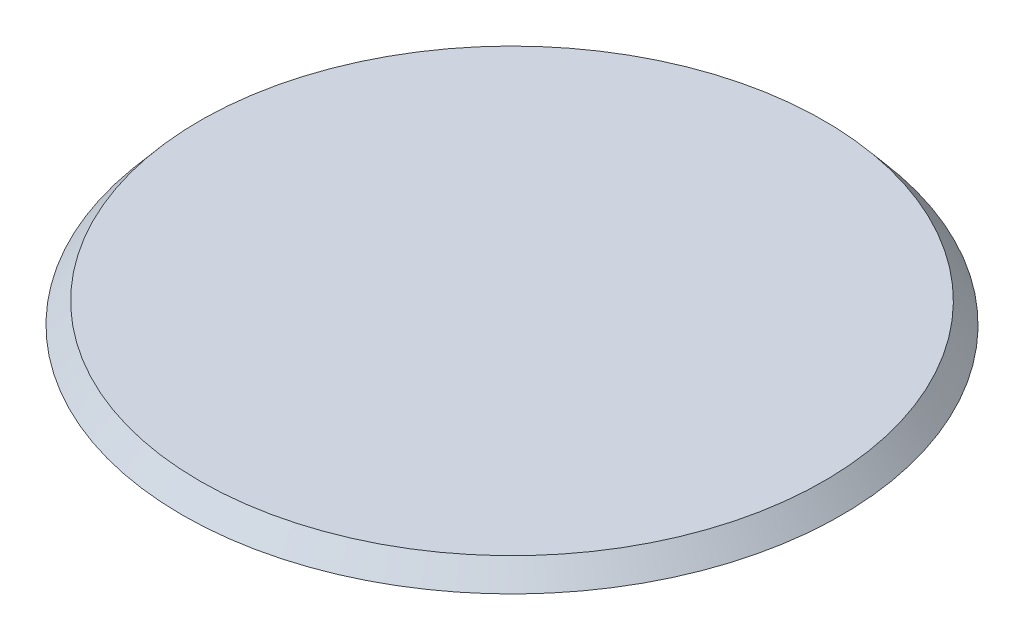
SolidWorks part; units mm, degrees
ref_plane "Front Plane" through (0, 0, 0) normal (0, 0, 1) x (1, 0, 0)
ref_plane "Top Plane" through (0, 0, 0) normal (0, 1, 0) x (1, 0, 0)
ref_plane "Right Plane" through (0, 0, 0) normal (1, 0, 0) x (0, 0, -1)
sketch "Sketch1" plane through (0, 0, 0) normal (0, 1, 0) x (1, 0, 0)
  circle A0 centre (0, 1.5051) radius 30
  dimension "D1" = 60
ref_plane "Plane1" through (0, 80, 0) normal (0, 1, 0) x (1, 0, 0)
sketch "Sketch2" plane through (0, 80, 0) normal (0, 1, 0) x (1, 0, 0)
  circle A0 centre (0, 0) radius 21.5
  dimension "D1" = 43
surface "Surface-Loft1"
sketch "Sketch4" plane through (0, 0, 0) normal (0, 1, 0) x (1, 0, 0)
  circle A0 centre (0, 0) radius 30
  dimension "D1" = 60
extrude "Boss-Extrude1" add sketch "Sketch4" against normal blind 2 draft 40 draft outward yes
other "3D Texture1"
other "Graphic (Open) -1"
